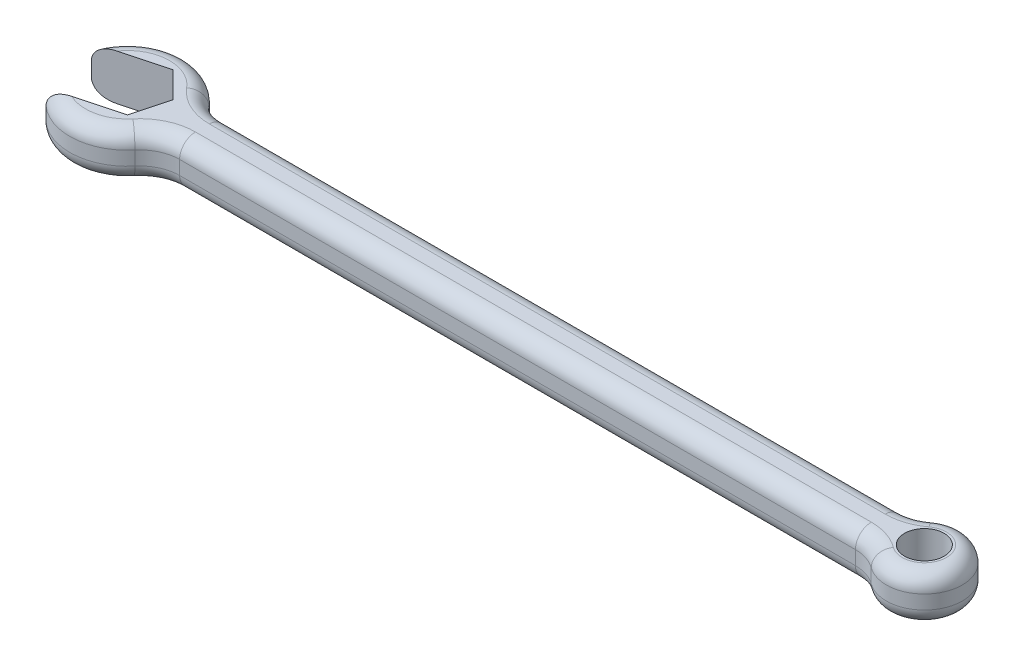
SolidWorks part; units mm, degrees
ref_plane "Front Plane" through (0, 0, 0) normal (0, 0, 1) x (1, 0, 0)
ref_plane "Top Plane" through (0, 0, 0) normal (0, 1, 0) x (1, 0, 0)
ref_plane "Right Plane" through (0, 0, 0) normal (1, 0, 0) x (0, 0, -1)
sketch "Sketch1" plane through (0, 0, 0) normal (0, 1, 0) x (1, 0, 0)
  line L0 (-191.0234, 18.013) -> (-223.4703, 9.3189)
  line L1 (-225, -11.5) -> (225, -11.5)
  line L2 (-225, -11.5) -> (-225, 11.5)
  line L3 (-225, 11.5) -> (225, 11.5)
  line L4 (225, -11.5) -> (225, 11.5)
  line L5 (-225, -11.5) -> (225, 11.5) construction
  line L6 (-225, 11.5) -> (225, -11.5) construction
  line L7 (-177.837, 4.8266) -> (-191.0234, 18.013)
  line L8 (-191.0234, 18.013) -> (-209.0364, 13.1864)
  line L9 (-209.0364, 13.1864) -> (-213.863, -4.8266)
  line L10 (-213.863, -4.8266) -> (-200.6766, -18.013)
  line L11 (-200.6766, -18.013) -> (-182.6636, -13.1864)
  line L12 (-182.6636, -13.1864) -> (-177.837, 4.8266)
  line L13 (-182.6636, -13.1864) -> (-215.1104, -21.8805)
  circle A0 centre (-195.85, 0) radius 29.15
  circle A1 centre (205.85, 0) radius 19.15
  circle A2 centre (205.85, 0) radius 10
  circle A3 centre (-195.85, 0) radius 16.15 construction
  point P0 (0, 0)
  dimension "D3" = 58.3
  dimension "D4" = 38.3
  dimension "D5" = 20
  dimension "D1" = 450
  dimension "D2" = 23
  dimension "D6" = 15
  dimension "D7" = 32.3
extrude "Boss-Extrude1" add sketch "Sketch1" along normal blind 23 contours A1 L3 A0 L1 | L3 A0 L0 L7 | L1 A0 L3 L7 L12 | L13 A0 L1 L12 L11 | L1 A1 L3 A2 | L1 A1 | L3 A1 | L3 A0 L0
fillet "Fillet1" radius 20 4 edges at (190.5375, 11.5, 11.5) (190.5375, 11.5, -11.5) (-169.0643, 11.5, -11.5) (-169.0643, 11.5, 11.5)
fillet "Fillet2" radius 8 18 edges at (-201.2158, 0, -28.6519) (-166.5958, 0, -13.3843) (-193.6173, 0, 29.0644) (-166.5958, 0, 13.3843) (12.2404, 0, 11.5) (188.8534, 0, 12.5021) (225, 0, 0) (188.8534, 0, -12.5021) (-201.2158, 23, -28.6519) (-166.5958, 23, -13.3843) (-193.6173, 23, 29.0644) (-166.5958, 23, 13.3843) (12.2404, 23, 11.5) (188.8534, 23, 12.5021) (225, 23, 0) (188.8534, 23, -12.5021) (12.2404, 0, -11.5) (12.2404, 23, -11.5)
